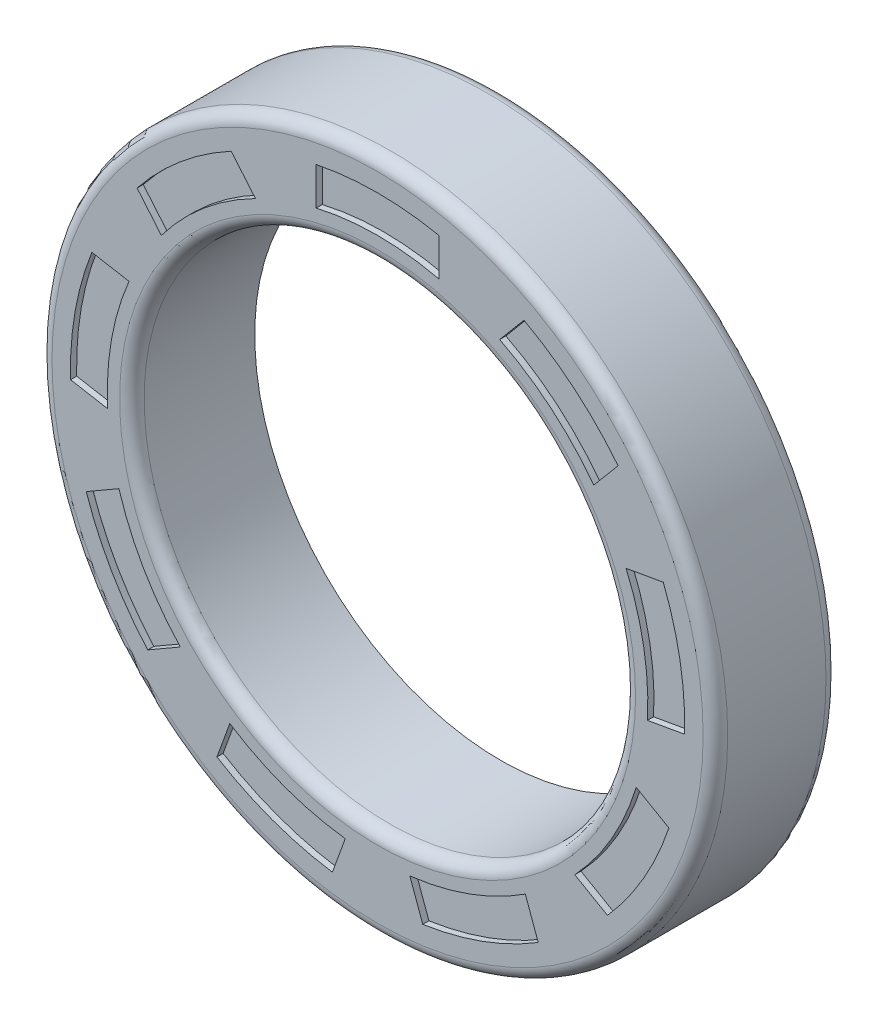
SolidWorks part; units mm, degrees
ref_plane "前视基准面" through (0, 0, 0) normal (0, 0, 1) x (1, 0, 0)
ref_plane "上视基准面" through (0, 0, 0) normal (0, 1, 0) x (1, 0, 0)
ref_plane "右视基准面" through (0, 0, 0) normal (1, 0, 0) x (0, 0, -1)
sketch "草图1" plane through (0, 0, 0) normal (0, 0, 1) x (1, 0, 0)
  circle A0 centre (0, 0) radius 27.5
  dimension "D1" = 55
extrude "拉伸1" add sketch "草图1" along normal blind 10
sketch "草图2" plane through (0, 0, 10) normal (0, 0, 1) x (1, 0, 0)
  circle A0 centre (0, 0) radius 20
  dimension "D1" = 40
extrude "切除-拉伸1" cut sketch "草图2" against normal blind 20
sketch "草图3" plane through (0, 0, 0) normal (0, 0, -1) x (-1, 0, 0)
  circle A0 centre (0, 0) radius 25.5
  circle A1 centre (0, 0) radius 22
  dimension "D1" = 44
  dimension "D2" = 51
extrude "切除-拉伸2" cut sketch "草图3" against normal blind 7
fillet "圆角1" radius 1 2 edges at (27.5, 0, 0) (27.5, 0, 10)
sketch "草图4" plane through (0, 0, 10) normal (0, 0, 1) x (1, 0, 0)
  line L0 (17.6015, 13.198) -> (19.5752, 15.5502)
  line L1 (5, 21.4243) -> (5, 24.4949)
  line L2 (-5, 21.4243) -> (-5, 24.4949)
  line L3 (9.941, 19.6259) -> (11.9148, 21.9781)
  line L4 (21.967, -1.2038) -> (24.991, -0.6705)
  line L5 (20.2306, 8.6443) -> (23.2545, 9.1775)
  line L6 (16.054, -15.0423) -> (18.7132, -16.5776)
  line L7 (21.054, -6.382) -> (23.7132, -7.9173)
  line L8 (2.6291, -21.8423) -> (3.6793, -24.7278)
  line L9 (12.026, -18.4221) -> (13.0762, -21.3076)
  line L10 (-12.026, -18.4221) -> (-13.0762, -21.3076)
  line L11 (-2.6291, -21.8423) -> (-3.6793, -24.7278)
  line L12 (-21.054, -6.382) -> (-23.7132, -7.9173)
  line L13 (-16.054, -15.0423) -> (-18.7132, -16.5776)
  line L14 (-20.2306, 8.6443) -> (-23.2545, 9.1775)
  line L15 (-21.967, -1.2038) -> (-24.991, -0.6705)
  line L16 (-9.941, 19.6259) -> (-11.9148, 21.9781)
  line L17 (-17.6015, 13.198) -> (-19.5752, 15.5502)
  arc A0 (5, 24.4949) -> (-5, 24.4949) centre (0, 0) ccw
  arc A1 (5, 21.4243) -> (-5, 21.4243) centre (0, 0) ccw
  arc A3 (19.5752, 15.5502) -> (11.9148, 21.9781) centre (0, 0) ccw
  arc A4 (17.6015, 13.198) -> (9.941, 19.6259) centre (0, 0) ccw
  arc A5 (24.991, -0.6705) -> (23.2545, 9.1775) centre (0, 0) ccw
  arc A6 (21.967, -1.2038) -> (20.2306, 8.6443) centre (0, 0) ccw
  arc A7 (18.7132, -16.5776) -> (23.7132, -7.9173) centre (0, 0) ccw
  arc A8 (16.054, -15.0423) -> (21.054, -6.382) centre (0, 0) ccw
  arc A9 (3.6793, -24.7278) -> (13.0762, -21.3076) centre (0, 0) ccw
  arc A10 (2.6291, -21.8423) -> (12.026, -18.4221) centre (0, 0) ccw
  arc A11 (-13.0762, -21.3076) -> (-3.6793, -24.7278) centre (0, 0) ccw
  arc A12 (-12.026, -18.4221) -> (-2.6291, -21.8423) centre (0, 0) ccw
  arc A13 (-23.7132, -7.9173) -> (-18.7132, -16.5776) centre (0, 0) ccw
  arc A14 (-21.054, -6.382) -> (-16.054, -15.0423) centre (0, 0) ccw
  arc A15 (-23.2545, 9.1775) -> (-24.991, -0.6705) centre (0, 0) ccw
  arc A16 (-20.2306, 8.6443) -> (-21.967, -1.2038) centre (0, 0) ccw
  arc A17 (-11.9148, 21.9781) -> (-19.5752, 15.5502) centre (0, 0) ccw
  arc A18 (-9.941, 19.6259) -> (-17.6015, 13.198) centre (0, 0) ccw
  dimension "D1" = 50
extrude "切除-拉伸3" cut sketch "草图4" against normal blind 0.5
fillet "圆角2" radius 1 1 edges at (20, 0, 10)
